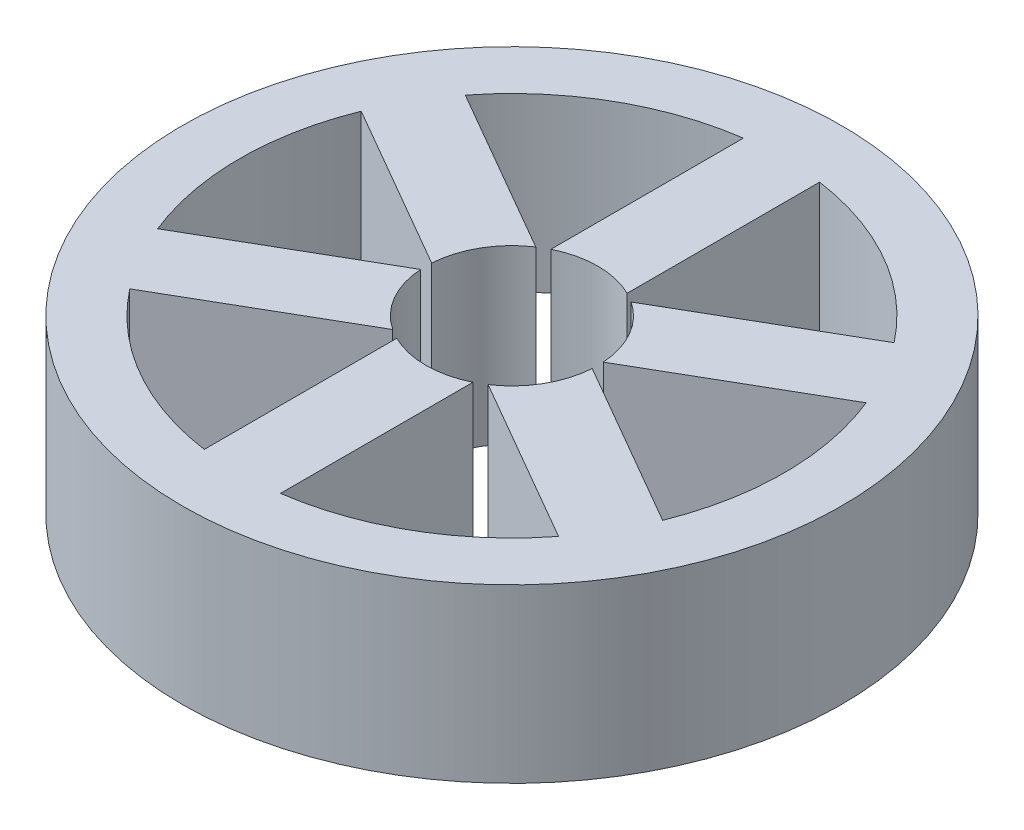
SolidWorks part; units mm, degrees
ref_plane "Front Plane" through (0, 0, 0) normal (0, 0, 1) x (1, 0, 0)
ref_plane "Top Plane" through (0, 0, 0) normal (0, 1, 0) x (1, 0, 0)
ref_plane "Right Plane" through (0, 0, 0) normal (1, 0, 0) x (0, 0, -1)
sketch "Sketch1" plane through (0, 0, 0) normal (0, 1, 0) x (1, 0, 0)
  line L6 (0.8322, -1.248) -> (3.7408, -2.9272)
  line L8 (-0.6647, -1.3447) -> (-0.6647, -4.7033)
  line L9 (-0.8322, -1.248) -> (-3.7408, -2.9272)
  line L11 (-0.3323, -0.5756) -> (-0.6647, -0.3837)
  line L13 (0.6647, 1.3447) -> (0.6647, 4.7033)
  line L14 (0.8322, 1.248) -> (3.7408, 2.9272)
  line L16 (-0.8322, 1.248) -> (-3.7408, 2.9272)
  line L17 (-0.6647, 1.3447) -> (-0.6647, 4.7033)
  line L18 (-1.4969, -0.0967) -> (-4.4055, -1.776)
  line L19 (0.6647, -1.3447) -> (0.6647, -4.7033)
  line L20 (1.4969, 0.0967) -> (4.4055, 1.776)
  line L21 (1.4969, -0.0967) -> (4.4055, -1.776)
  line L26 (-1.4969, 0.0967) -> (-4.4055, 1.776)
  circle A0 centre (0, 0) radius 5.75
  arc A1 (-4.4055, 1.776) -> (-4.4055, -1.776) centre (0, 0) ccw
  circle A2 centre (0, 0) radius 1.5
  arc A3 (-0.6647, 4.7033) -> (-3.7408, 2.9272) centre (0, 0) ccw
  arc A4 (3.7408, 2.9272) -> (0.6647, 4.7033) centre (0, 0) ccw
  arc A5 (4.4055, -1.776) -> (4.4055, 1.776) centre (0, 0) ccw
  arc A6 (0.6647, -4.7033) -> (3.7408, -2.9272) centre (0, 0) ccw
  arc A7 (-3.7408, -2.9272) -> (-0.6647, -4.7033) centre (0, 0) ccw
  point P32 (0, 0)
  dimension "D1" = 11.5
  dimension "D2" = 9.5
  dimension "D3" = 3
extrude "Boss-Extrude1" add sketch "Sketch1" along normal blind 3 contours A0 A7 L9 A2 L18 A1 L26 L16 A3 L17 L13 A4 L14 L20 A5 L21 L6 A6 L19 L8
